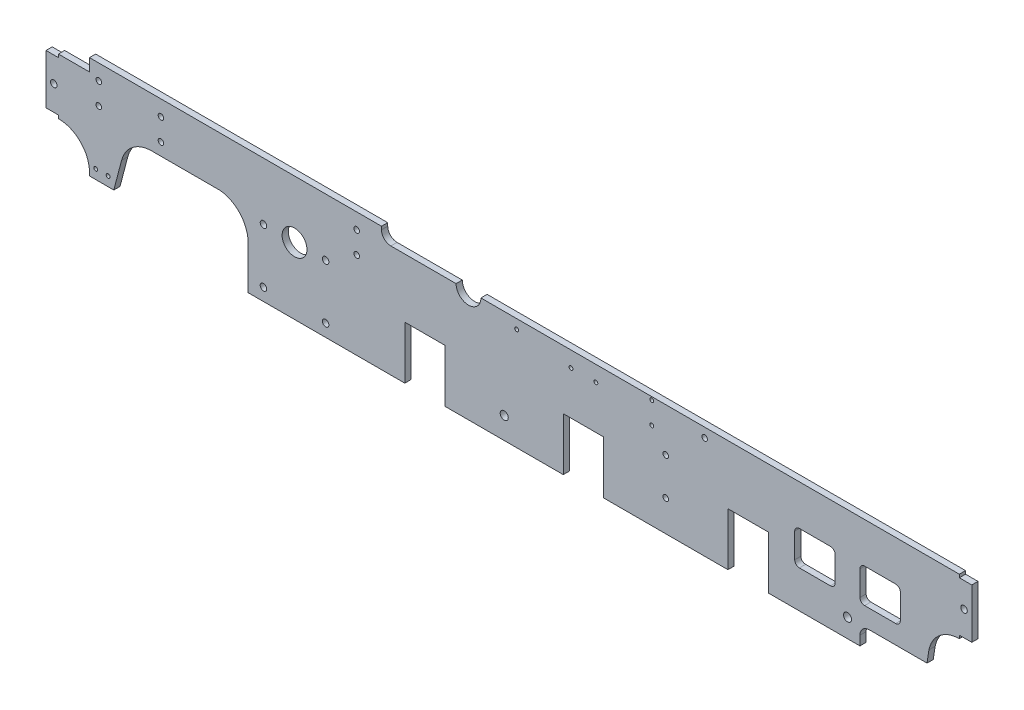
SolidWorks part; units mm, degrees
ref_plane "Plan de face" through (0, 0, 0) normal (0, 0, 1) x (1, 0, 0)
ref_plane "Plan de dessus" through (0, 0, 0) normal (0, 1, 0) x (1, 0, 0)
ref_plane "Plan de droite" through (0, 0, 0) normal (1, 0, 0) x (0, 0, -1)
sketch "Esquisse1" plane through (0, 0, 0) normal (0, 0, 1) x (1, 0, 0)
  line L0 (-149, 15) -> (-149, -1)
  line L1 (-149, 20) -> (149, 20)
  line L2 (-149, 20) -> (-149, -20)
  line L3 (-149, -20) -> (149, -20)
  line L4 (149, 20) -> (149, -20)
  line L5 (-149, 20) -> (-145, 20)
  line L6 (-149, 20) -> (-149, 15)
  line L7 (-149, 15) -> (-145, 15)
  line L8 (-145, 20) -> (-145, 15)
  line L9 (-149, -2) -> (-149, -12)
  line L10 (-149, -1) -> (-145, -1)
  line L11 (-149, -1) -> (-149, -2)
  line L12 (-149, -2) -> (-145, -2)
  line L13 (-145, -1) -> (-145, -2)
  line L14 (-149, -12) -> (-145, -12) construction
  line L15 (-149, -20) -> (-115, -20)
  line L16 (-149, -12) -> (-149, -13) construction
  line L17 (-135, -13) -> (-127.1683, -13)
  line L18 (-135, -12) -> (-135, -13)
  line L19 (-115, -20) -> (-115, 20) construction
  line L20 (-115, 20) -> (-115, -6) construction
  line L21 (-149, -20) -> (-129, -20)
  line L22 (-115, -6) -> (-94, -6) construction
  line L23 (-115, 4) -> (-92.9165, 4)
  line L24 (-127.1683, -13) -> (-124.6743, -3.4686)
  line L25 (-84, -7.0835) -> (-84, -20)
  line L26 (149, -20) -> (-33.5, -20)
  line L27 (149, -20) -> (-20.5, -20)
  line L28 (-33.5, -20) -> (-20.5, -20)
  line L29 (-33.5, -20) -> (-33.5, -3)
  line L30 (-20.5, -20) -> (-20.5, -3)
  line L31 (-33.5, -3) -> (-20.5, -3)
  line L32 (149, -20) -> (17.5, -20) construction
  line L33 (149, -20) -> (30.5, -20) construction
  line L34 (17.5, -20) -> (30.5, -20)
  line L35 (17.5, -20) -> (17.5, -3)
  line L36 (30.5, -20) -> (30.5, -3)
  line L37 (17.5, -3) -> (30.5, -3)
  line L38 (149, -20) -> (70.5, -20) construction
  line L39 (149, -20) -> (83.5, -20) construction
  line L40 (70.5, -20) -> (83.5, -20)
  line L41 (70.5, -20) -> (70.5, -3)
  line L42 (83.5, -20) -> (83.5, -3)
  line L43 (70.5, -3) -> (83.5, -3)
  line L44 (149, -20) -> (113, -20) construction
  line L45 (113, -20) -> (149, -20)
  line L46 (113, -20) -> (113, -17)
  line L47 (149, -20) -> (149, -14)
  line L49 (145, -20) -> (145, 20) construction
  line L50 (135.202, -10) -> (134.5962, -14)
  line L51 (145, -2) -> (149, -2)
  line L52 (145, -2) -> (145, -1)
  line L53 (149, -2) -> (149, -1)
  line L54 (145, -1) -> (149, -1)
  line L55 (116, -14) -> (134.5962, -14)
  line L56 (149, 16) -> (-38, 16)
  line L57 (-41, 19) -> (-41, 20)
  line L58 (149, 16) -> (145, 16)
  line L59 (149, 16) -> (149, 15)
  line L60 (145, 16) -> (145, 15)
  line L61 (149, 15) -> (145, 15)
  line L62 (-149, 20) -> (-135, 20)
  line L63 (-149, 20) -> (-149, 16)
  line L64 (-135, 20) -> (-135, 16)
  line L65 (-149, 16) -> (-135, 16)
  line L66 (105, 1.5) -> (105, -6.5)
  line L67 (124.5, 3) -> (114.5, 3)
  line L68 (126, 1.5) -> (126, -6.5)
  line L69 (124.5, -8) -> (114.5, -8)
  line L70 (113, 1.5) -> (113, -6.5)
  line L71 (103.5, 3) -> (93.5, 3)
  line L72 (92, 1.5) -> (92, -6.5)
  line L73 (103.5, -8) -> (93.5, -8)
  line L74 (46, 20) -> (46, -1.7321) construction
  line L75 (-132, 20) -> (-132, 6.0941) construction
  line L76 (-49, 20) -> (-49, 4.1116) construction
  arc A0 (-145, -2) -> (-135, -12) centre (-145, -12) cw
  arc A1 (113, -17) -> (116, -14) centre (116, -17) cw
  arc A2 (-84, -7.0835) -> (-92.9165, 4) centre (-94, -6) ccw
  arc A3 (-115, 4) -> (-124.6743, -3.4686) centre (-115, -6) ccw
  arc A4 (145, -2) -> (135.202, -10) centre (145, -12) ccw
  arc A5 (-17.0037, 16) -> (-9.0037, 16) centre (-13.0037, 16) ccw
  arc A6 (-41, 19) -> (-38, 16) centre (-38, 19) ccw
  arc A7 (113, 1.5) -> (114.5, 3) centre (114.5, 1.5) cw
  arc A8 (126, 1.5) -> (124.5, 3) centre (124.5, 1.5) ccw
  arc A9 (124.5, -8) -> (126, -6.5) centre (124.5, -6.5) ccw
  arc A10 (114.5, -8) -> (113, -6.5) centre (114.5, -6.5) cw
  arc A11 (103.5, -8) -> (105, -6.5) centre (103.5, -6.5) ccw
  arc A12 (105, 1.5) -> (103.5, 3) centre (103.5, 1.5) ccw
  arc A13 (92, 1.5) -> (93.5, 3) centre (93.5, 1.5) cw
  arc A14 (93.5, -8) -> (92, -6.5) centre (93.5, -6.5) cw
  circle A15 centre (-69, 1.5) radius 4
  circle A16 centre (146.5, 7) radius 1.05
  circle A17 centre (109, -14) radius 1.3
  circle A18 centre (63, 13) radius 0.9
  circle A19 centre (46, 15) radius 0.625
  circle A20 centre (46, 8) radius 0.625
  circle A21 centre (28, 11) radius 0.625
  circle A22 centre (20, 11) radius 0.625
  circle A23 centre (2.5, 13) radius 0.625
  circle A24 centre (-1.5, -13) radius 1.3
  circle A25 centre (-59, -16) radius 1.05
  circle A26 centre (-79, -16) radius 1.05
  circle A27 centre (-79, 1.5) radius 1.05
  circle A28 centre (-59, 1.5) radius 1.05
  circle A29 centre (-146.5, 7) radius 1.05
  circle A30 centre (-133, -10) radius 0.625
  circle A31 centre (-129, -10) radius 0.625
  circle A32 centre (-132, 15) radius 0.9
  circle A33 centre (-132, 8) radius 0.9
  circle A34 centre (-112, 15) radius 0.9
  circle A35 centre (-112, 8) radius 0.9
  circle A36 centre (-49, 8) radius 0.9
  circle A37 centre (-49, 15) radius 0.9
  circle A38 centre (50.5, -10) radius 0.9
  circle A39 centre (50.5, 2) radius 0.9
  point P38 (149, -14)
  point P45 (145, -20)
  point P48 (145, -12)
  point P53 (149, 16)
  point P56 (149, 20)
  point P63 (-13.0037, 16)
  point P71 (-41, 16)
  point P73 (126, 3)
  point P82 (113, 3)
  point P85 (126, 3)
  point P90 (113, -8)
  point P91 (-69, 1.5)
  point P106 (146.5, 7)
  point P109 (109, -14)
  point P112 (63, 13)
  point P115 (46, 15)
  point P120 (28, 11)
  point P134 (-146.5, 7)
  point P146 (-132, 20)
  point P152 (-49, 20)
  dimension "D11" = 10
  dimension "D17" = 10
  dimension "D18" = 10.0585
  dimension "D33" = 3
  dimension "D37" = 10
  dimension "D39" = 6
  dimension "D44" = 4
  dimension "D45" = 3
  dimension "D51" = 1.5
  dimension "D52" = 1.5
  dimension "D57" = 8
  dimension "D60" = 2.1
  dimension "D63" = 2.6
  dimension "D66" = 1.8
  dimension "D69" = 1.25
  dimension "D74" = 1.25
  dimension "D76" = 1.25
  dimension "D80" = 2.6
  dimension "D86" = 2.1
  dimension "D89" = 2.5
  dimension "D91" = 2.1
  dimension "D95" = 1.25
  dimension "D98" = 1.8
  dimension "D104" = 1.8
  dimension "D105" = 1.8
  dimension "D109" = 1.8
  dimension "D110" = 1.8
  dimension "D1" = 298
  dimension "D2" = 40
  dimension "D3" = 20
  dimension "D4" = 149
  dimension "D5" = 5
  dimension "D6" = 4
  dimension "D7" = 16
  dimension "D8" = 1
  dimension "D9" = 4
  dimension "D10" = 10
  dimension "D12" = 33
  dimension "D13" = 34
  dimension "D14" = 26
  dimension "D15" = 2
  dimension "D16" = 55
  dimension "D19" = 16
  dimension "D20" = 1
  dimension "D21" = 65
  dimension "D22" = 182.5
  dimension "D23" = 169.5
  dimension "D24" = 17
  dimension "D25" = 131.5
  dimension "D26" = 118.5
  dimension "D27" = 23
  dimension "D28" = 78.5
  dimension "D29" = 65.5
  dimension "D30" = 17
  dimension "D31" = 36
  dimension "D32" = 4
  dimension "D34" = 34
  dimension "D35" = 32
  dimension "D36" = 10
  dimension "D38" = 1
  dimension "D40" = 4
  dimension "D41" = 190
  dimension "D42" = 1
  dimension "D43" = 136
  dimension "D46" = 4
  dimension "D47" = 23
  dimension "D48" = 17
  dimension "D49" = 28
  dimension "D50" = 36
  dimension "D54" = 44
  dimension "D55" = 18.5
  dimension "D56" = 218
  dimension "D58" = 2.5
  dimension "D59" = 8
  dimension "D61" = 34
  dimension "D62" = 40
  dimension "D64" = 86
  dimension "D65" = 7
  dimension "D67" = 103
  dimension "D68" = 5
  dimension "D71" = 12
  dimension "D72" = 5
  dimension "D73" = 121
  dimension "D75" = 129
  dimension "D77" = 146.5
  dimension "D78" = 7
  dimension "D79" = 150.5
  dimension "D81" = 7
  dimension "D82" = 4
  dimension "D83" = 208
  dimension "D87" = 4
  dimension "D88" = 18.5
  dimension "D90" = 8
  dimension "D92" = 16
  dimension "D93" = 30
  dimension "D94" = 20
  dimension "D96" = 17
  dimension "D97" = 5
  dimension "D100" = 12
  dimension "D102" = 37
  dimension "D103" = 100
  dimension "D106" = 5
  dimension "D107" = 12
  dimension "D108" = 52
  dimension "D111" = 12
  dimension "D112" = 30
  dimension "D53" = 2
  dimension "D70" = 2
  dimension "D85" = 2
  dimension "D84" = 2
  dimension "D99" = 2
  dimension "D101" = 2
extrude "Boss.-Extru.1" add sketch "Esquisse1" along normal blind 2 contours A6 L57 L1 L64 L65 L8 L7 L0 L10 L13 A0 L18 L17 L24 A3 L23 A2 L25 L3 L29 L31 L30 L26 L35 L37 L36 L41 L43 L42 L46 A1 L55 L50 A4 L52 L54 L4 L61 L60 L56 A5 A37 A36 A35
